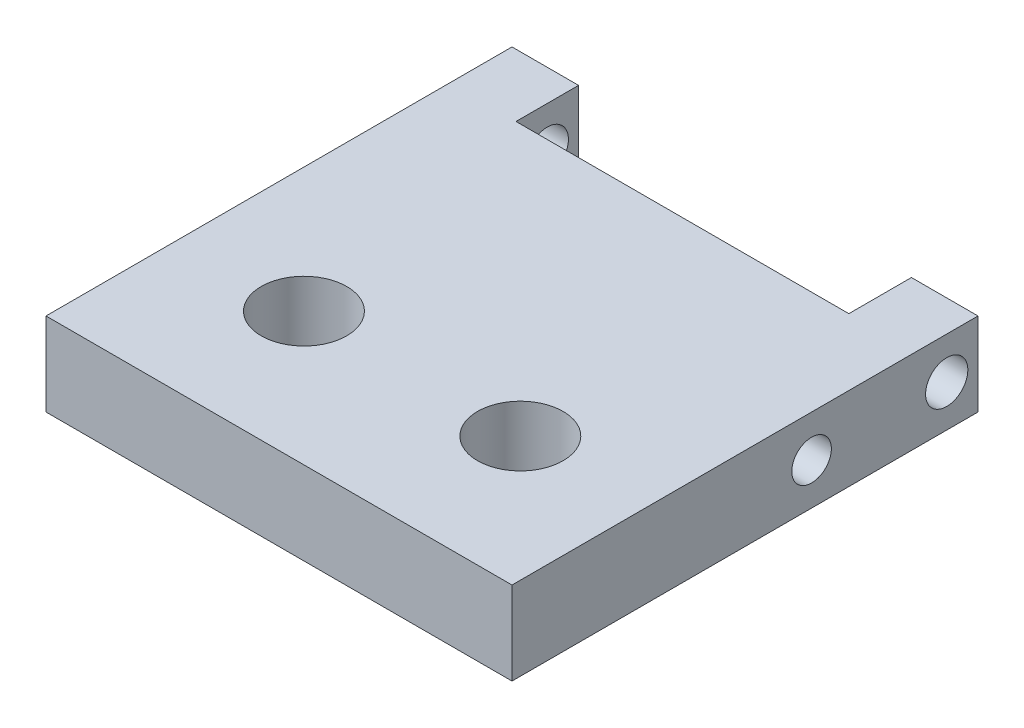
SolidWorks part; units mm, degrees
material "6061 Alloy"
ref_plane "Front Plane" through (0, 0, 0) normal (0, 0, 1) x (1, 0, 0)
ref_plane "Top Plane" through (0, 0, 0) normal (0, 1, 0) x (1, 0, 0)
ref_plane "Right Plane" through (0, 0, 0) normal (1, 0, 0) x (0, 0, -1)
sketch "Sketch1" plane through (0, 0, 0) normal (0, 1, 0) x (1, 0, 0)
  line L1 (-8.89, -8.89) -> (8.89, -8.89)
  line L2 (-8.89, -8.89) -> (-8.89, 8.89)
  line L3 (-8.89, 8.89) -> (8.89, 8.89)
  line L4 (8.89, -8.89) -> (8.89, 8.89)
  line L5 (-8.89, -8.89) -> (8.89, 8.89) construction
  line L6 (-8.89, 8.89) -> (8.89, -8.89) construction
  point P0 (0, 0)
  dimension "D1" = 17.78
  dimension "D2" = 17.78
extrude "Boss-Extrude1" add sketch "Sketch1" along normal blind 3.175
sketch "Sketch2" plane through (0, 3.175, 0) normal (0, 1, 0) x (1, 0, 0)
  line L0 (8.89, 8.89) -> (-8.89, 8.89) construction
  line L1 (-6.35, 11.2776) -> (6.35, 11.2776)
  line L2 (-6.35, 11.2776) -> (-6.35, 6.5024)
  line L3 (-6.35, 6.5024) -> (6.35, 6.5024)
  line L4 (6.35, 11.2776) -> (6.35, 6.5024)
  line L5 (-6.35, 11.2776) -> (6.35, 6.5024) construction
  line L6 (-6.35, 6.5024) -> (6.35, 11.2776) construction
  line L7 (-8.89, 8.89) -> (-8.89, -8.89) construction
  point P0 (0, 8.89)
  dimension "D1" = 2.3876
  dimension "D2" = 2.54
extrude "Cut-Extrude1" cut sketch "Sketch2" against normal through all contours L1 L4 L3 L2
hole_wizard "#4 Clearance Hole1" positions "Sketch6" profile "Sketch7" hole size "#4" standard "ANSI Inch" end condition through all
sketch "Sketch6" plane through (0, 3.175, 0) normal (0, 1, 0) x (1, 0, 0)
  line L0 (8.89, 8.89) -> (6.35, 8.89) construction
  line L2 (8.89, -8.89) -> (8.89, 8.89) construction
  line L3 (-8.89, 8.89) -> (-8.89, -8.89) construction
  point P0 (4.1275, -3.81)
  point P9 (-4.1275, -3.81)
  dimension "D1" = 12.7
  dimension "D2" = 4.7625
  dimension "D3" = 4.7625
sketch "Sketch7" plane through (4.1275, 3.175, 3.81) normal (1, 0, 0) x (0, 0, 1)
  line L0 (0, 0) -> (0, 3.175)
  line L1 (0, 3.175) -> (1.6319, 3.175)
  line L2 (1.6319, 3.175) -> (1.6319, 0)
  line L5 (1.6319, 0) -> (0, 0)
  line L11 (0, -6.35) -> (0, 107.95) construction
  dimension "Thru Hole Dia." = 3.2639
  dimension "Thru Hole Depth" = 3.175
hole_wizard "#0 Clearance Hole1" positions "Sketch10" profile "Sketch11" hole size "#0" standard "ANSI Inch" end condition through all
sketch "Sketch10" plane through (8.89, 0, 0) normal (1, 0, 0) x (0, 0, -1)
  line L0 (-8.89, 3.175) -> (8.89, 3.175) construction
  line L1 (8.89, 3.175) -> (8.89, 0) construction
  point P0 (7.6962, 1.5875)
  dimension "D1" = 1.5875
  dimension "D2" = 1.1938
sketch "Sketch11" plane through (8.89, 1.5875, -7.6962) normal (0, 1, 0) x (0, 0, -1)
  line L0 (0, 0) -> (0, 17.78)
  line L1 (0, 17.78) -> (0.8064, 17.78)
  line L2 (0.8064, 17.78) -> (0.8064, 0)
  line L5 (0.8064, 0) -> (0, 0)
  line L11 (0, -6.35) -> (0, 107.95) construction
  dimension "Thru Hole Dia." = 1.6129
  dimension "Thru Hole Depth" = 17.78
hole_wizard "#1-72 Tapped Hole1" positions "Sketch14" profile "Sketch15" tap size "#1-72" standard "ANSI Inch" end condition through all
sketch "Sketch14" plane through (8.89, 0, 0) normal (1, 0, 0) x (0, 0, -1)
  line L1 (-8.89, 3.175) -> (8.89, 3.175) construction
  line L2 (8.89, 3.175) -> (8.89, 0) construction
  point P0 (2.54, 1.5875)
  dimension "D1" = 1.5875
  dimension "D2" = 6.35
cosmetic thread "Hole Thread1"
sketch "Sketch15" plane through (8.89, 1.5875, -2.54) normal (0, 1, 0) x (0, 0, -1)
  line L0 (0, 0) -> (0, 17.78)
  line L1 (0, 17.78) -> (0.7556, 17.78)
  line L2 (0.7556, 17.78) -> (0.7556, 0)
  line L5 (0.7556, 0) -> (0, 0)
  line L11 (0, -6.35) -> (0, 107.95) construction
  dimension "Thru Tap Drill Dia." = 1.5113
  dimension "Thru Tap Drill Depth" = 17.78
